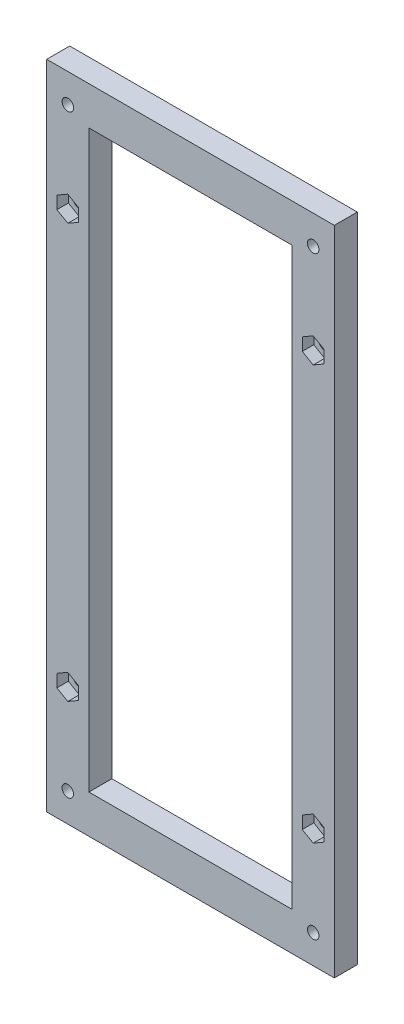
SolidWorks part; units mm, degrees
ref_plane "Front Plane" through (0, 0, 0) normal (1, 0, 0) x (0, 1, 0)
ref_plane "Top Plane" through (0, 0, 0) normal (0, 0, 1) x (0, 1, 0)
ref_plane "Right Plane" through (0, 0, 0) normal (0, 1, 0) x (-1, 0, 0)
sketch "Sketch1" plane through (0, 0, 0) normal (0, 0, 1) x (0, 1, 0)
  line L1 (-85, -37.5) -> (85, -37.5)
  line L2 (-85, -37.5) -> (-85, 37.5)
  line L3 (-85, 37.5) -> (85, 37.5)
  line L4 (85, -37.5) -> (85, 37.5)
  line L5 (-85, -37.5) -> (85, 37.5) construction
  line L6 (-85, 37.5) -> (85, -37.5) construction
  point P0 (0, 0)
  dimension "D1" = 170
  dimension "D2" = 75
extrude "Boss-Extrude1" add sketch "Sketch1" along normal blind 6
sketch "Sketch2" plane through (0, 0, 6) normal (0, 0, 1) x (1, 0, 0)
  line L0 (0, 85) -> (0, -85) construction
  line L1 (37.5, 85) -> (-37.5, 85) construction
  line L2 (-37.5, -85) -> (37.5, -85) construction
  line L3 (-37.5, 0) -> (37.5, 0) construction
  line L4 (-37.5, 85) -> (-37.5, -85) construction
  line L5 (37.5, -85) -> (37.5, 85) construction
  line L6 (-32, 85) -> (-32, -85) construction
  circle A0 centre (-32, 54) radius 1.5
  circle A1 centre (-32, -54) radius 1.5
  circle A2 centre (-32, -77.5) radius 1.5
  circle A6 centre (-32, 77.5) radius 1.5
  circle A7 centre (32, -77.5) radius 1.5
  circle A8 centre (32, -54) radius 1.5
  circle A9 centre (32, 54) radius 1.5
  circle A10 centre (32, 77.5) radius 1.5
  point P20 (0, 0)
  point P21 (0, 0)
  dimension "D2" = 3
  dimension "D1" = 32
  dimension "D3" = 155
  dimension "D4" = 108
extrude "Cut-Extrude1" cut sketch "Sketch2" against normal through all
sketch "Sketch5" plane through (0, 0, 6) normal (0, 0, 1) x (1, 0, 0)
  line L0 (-32, -57.2909) -> (-32, -54) construction
  line L1 (-29.15, -55.6454) -> (-29.15, -52.3546)
  line L2 (-29.15, -52.3546) -> (-32, -50.7091)
  line L3 (-32, -50.7091) -> (-34.85, -52.3546)
  line L4 (-34.85, -52.3546) -> (-34.85, -55.6454)
  line L5 (-34.85, -55.6454) -> (-32, -57.2909)
  line L6 (-32, -57.2909) -> (-29.15, -55.6454)
  line L7 (0, -85) -> (0, 85) construction
  line L8 (-37.5, -85) -> (37.5, -85) construction
  line L9 (37.5, 85) -> (-37.5, 85) construction
  line L10 (32, -57.2909) -> (29.15, -55.6454)
  line L11 (34.85, -55.6454) -> (32, -57.2909)
  line L12 (34.85, -52.3546) -> (34.85, -55.6454)
  line L13 (32, -50.7091) -> (34.85, -52.3546)
  line L14 (29.15, -52.3546) -> (32, -50.7091)
  line L15 (29.15, -55.6454) -> (29.15, -52.3546)
  line L16 (-32, 54) -> (-32, 50.7091) construction
  line L17 (-29.15, 55.6454) -> (-32, 57.2909)
  line L18 (-32, 57.2909) -> (-34.85, 55.6454)
  line L19 (-34.85, 55.6454) -> (-34.85, 52.3546)
  line L20 (-34.85, 52.3546) -> (-32, 50.7091)
  line L21 (-32, 50.7091) -> (-29.15, 52.3546)
  line L22 (-29.15, 52.3546) -> (-29.15, 55.6454)
  line L23 (29.15, 52.3546) -> (29.15, 55.6454)
  line L24 (32, 50.7091) -> (29.15, 52.3546)
  line L25 (34.85, 52.3546) -> (32, 50.7091)
  line L26 (34.85, 55.6454) -> (34.85, 52.3546)
  line L27 (32, 57.2909) -> (34.85, 55.6454)
  line L28 (29.15, 55.6454) -> (32, 57.2909)
  circle A0 centre (-32, -54) radius 2.85 construction
  circle A1 centre (-32, 54) radius 2.85 construction
  dimension "D1" = 5.7
extrude "Cut-Extrude3" cut sketch "Sketch5" against normal blind 3
sketch "Sketch6" plane through (0, 0, 6) normal (0, 0, 1) x (1, 0, 0)
  line L0 (37.5, 85) -> (-37.5, 85) construction
  line L1 (26.5, -75) -> (-26.5, -75)
  line L2 (26.5, -75) -> (26.5, 75)
  line L3 (26.5, 75) -> (-26.5, 75)
  line L4 (-26.5, -75) -> (-26.5, 75)
  line L5 (26.5, -75) -> (-26.5, 75) construction
  line L6 (26.5, 75) -> (-26.5, -75) construction
  line L7 (37.5, -85) -> (37.5, 85) construction
  point P0 (0, 0)
  dimension "D1" = 10
  dimension "D2" = 11
extrude "Cut-Extrude4" cut sketch "Sketch6" against normal blind 10
